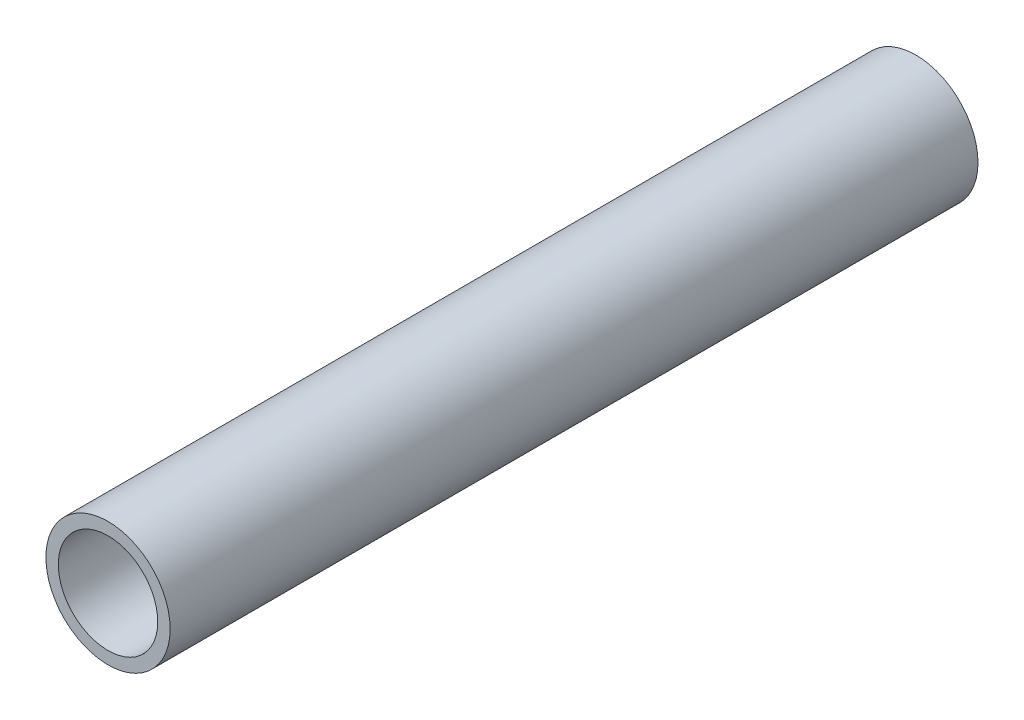
SolidWorks part; units mm, degrees
ref_plane "Front Plane" through (0, 0, 0) normal (0, 0, 1) x (1, 0, 0)
ref_plane "Top Plane" through (0, 0, 0) normal (0, 1, 0) x (1, 0, 0)
ref_plane "Right Plane" through (0, 0, 0) normal (1, 0, 0) x (0, 0, -1)
sketch "Sketch1" plane through (0, 0, 0) normal (0, 0, 1) x (1, 0, 0)
  circle A0 centre (0, 0) radius 4
  circle A1 centre (0, 0) radius 5
  dimension "D1" = 8
  dimension "D2" = 10
extrude "Boss-Extrude1" add sketch "Sketch1" along normal mid plane 65
